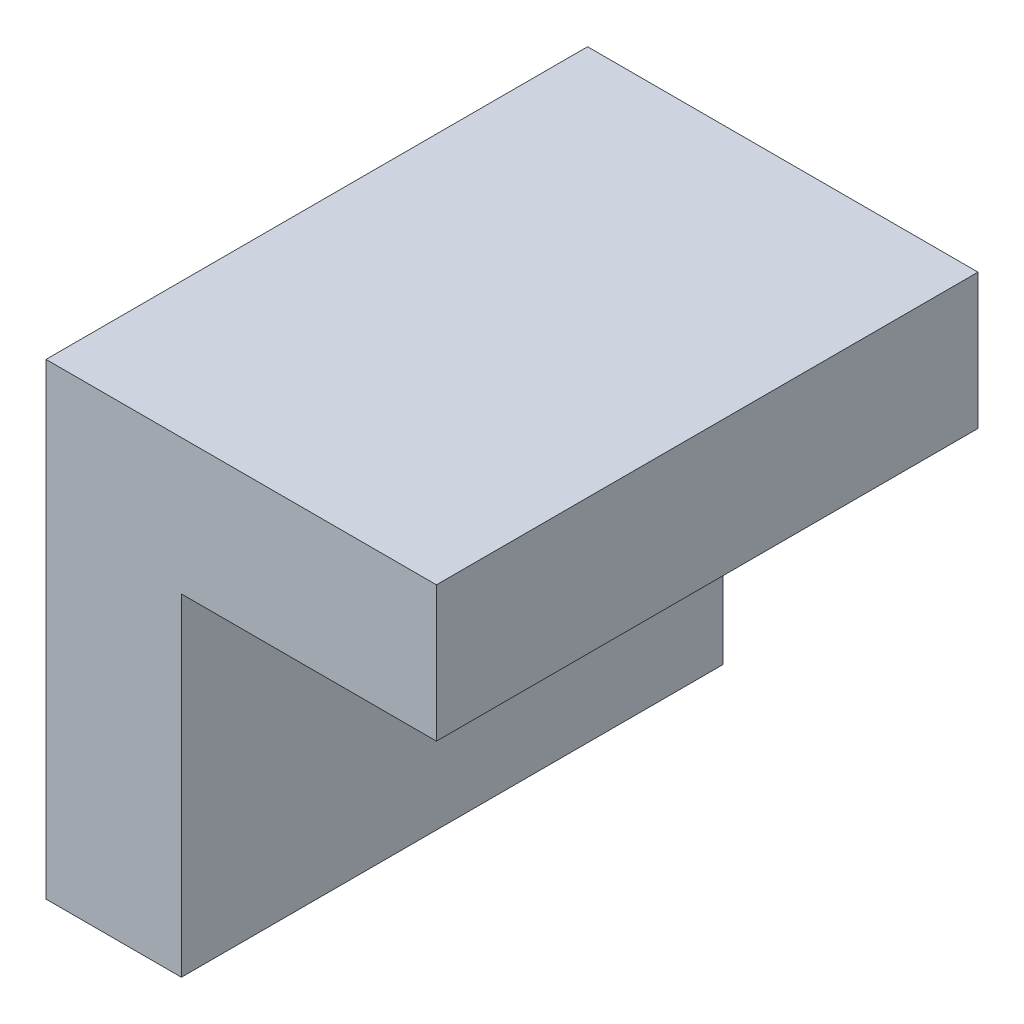
SolidWorks part; units mm, degrees
ref_plane "정면" through (0, 0, 0) normal (0, 0, 1) x (1, 0, 0)
ref_plane "윗면" through (0, 0, 0) normal (0, 1, 0) x (1, 0, 0)
ref_plane "우측면" through (0, 0, 0) normal (1, 0, 0) x (0, 0, -1)
sketch "Sketch1" plane through (0, 0, 0) normal (0, 0, 1) x (1, 0, 0)
  line L0 (0, 0) -> (0, 59.0449)
  line L1 (0, 59.0449) -> (47.6748, 59.0449)
extrude "Extrude-Thin1" add sketch "Sketch1" along normal blind 80 thin thin type mid plane wall 20
